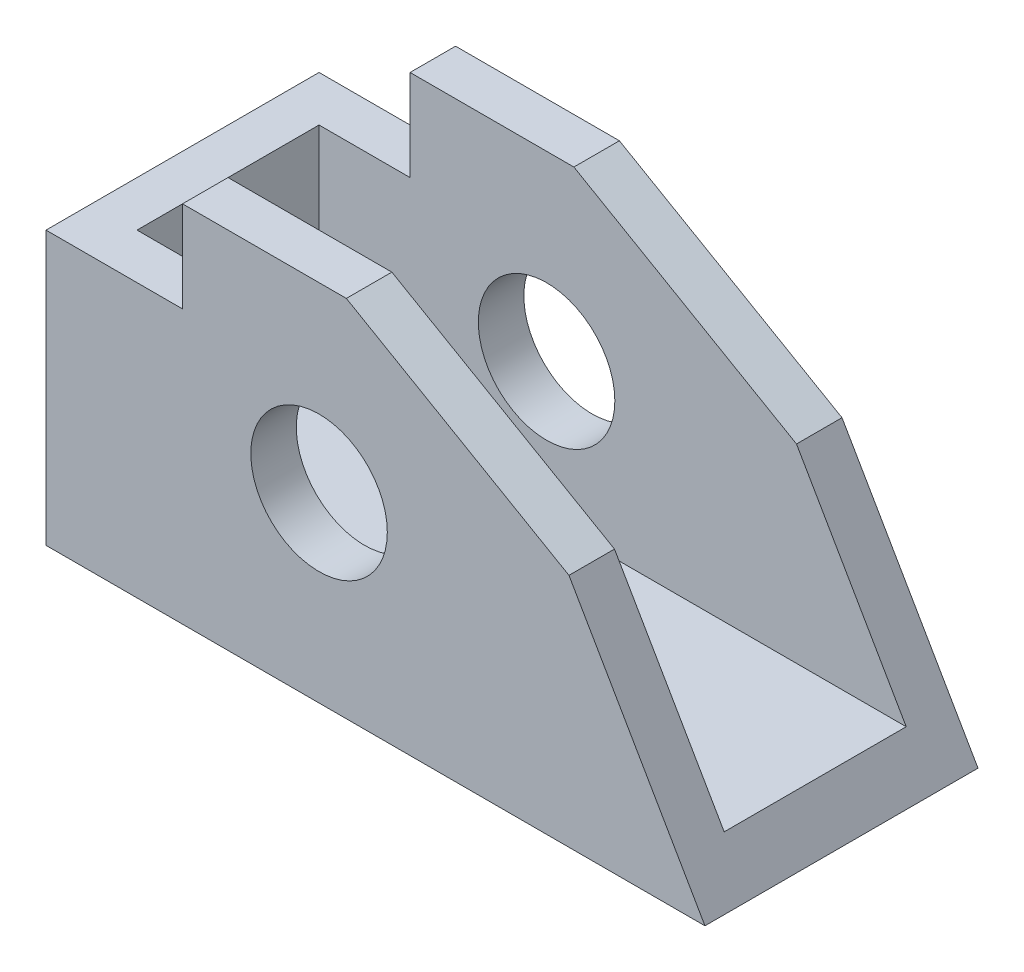
SolidWorks part; units mm, degrees
ref_plane "Front Plane" through (0, 0, 0) normal (0, 0, 1) x (1, 0, 0)
ref_plane "Top Plane" through (0, 0, 0) normal (0, 1, 0) x (1, 0, 0)
ref_plane "Right Plane" through (0, 0, 0) normal (1, 0, 0) x (0, 0, -1)
sketch "Sketch1" plane through (0, 0, 0) normal (0, 1, 0) x (1, 0, 0)
  line L1 (-96.8613, 47.6118) -> (-4.9133, 47.6118)
  line L2 (-96.8613, 47.6118) -> (-96.8613, 9.5118)
  line L3 (-96.8613, 9.5118) -> (-4.9133, 9.5118)
  line L4 (-4.9133, 47.6118) -> (-4.9133, 9.5118)
  dimension "D1" = 91.948
  dimension "D2" = 38.1
extrude "Boss-Extrude1" add sketch "Sketch1" along normal blind 50.8
sketch "Sketch2" plane through (0, 0, -9.5118) normal (0, 0, 1) x (1, 0, 0)
  line L0 (-96.8613, 0) -> (-4.9133, 0) construction
  line L1 (-96.8613, 50.8) -> (-96.8613, 0) construction
  circle A0 centre (-58.7613, 25.4) radius 9.525
  dimension "D1" = 19.05
  dimension "D2" = 25.4
  dimension "D3" = 38.1
extrude "Cut-Extrude1" cut sketch "Sketch2" against normal through all
sketch "Sketch3" plane through (0, 0, -9.5118) normal (0, 0, 1) x (1, 0, 0)
  line L0 (-96.8613, 38.1) -> (-77.8113, 38.1)
  line L1 (-96.8613, 50.8) -> (-96.8613, 0) construction
  line L2 (-77.8113, 38.1) -> (-77.8113, 50.8)
  line L3 (-96.8613, 50.8) -> (-4.9133, 50.8) construction
  line L4 (-77.8113, 50.8) -> (-96.8613, 50.8)
  line L5 (-96.8613, 50.8) -> (-96.8613, 38.1)
  dimension "D1" = 12.7
  dimension "D2" = 19.05
extrude "Cut-Extrude2" cut sketch "Sketch3" against normal through all contours L5 L0 L2 L4
sketch "Sketch4" plane through (0, 50.8, 0) normal (0, 1, 0) x (1, 0, 0)
  line L0 (-77.8113, 47.6118) -> (-77.8113, 9.5118) construction
  line L1 (-77.8113, 41.2618) -> (-4.9133, 41.2618)
  line L2 (-77.8113, 41.2618) -> (-77.8113, 15.8618)
  line L3 (-77.8113, 15.8618) -> (-4.9133, 15.8618)
  line L4 (-4.9133, 41.2618) -> (-4.9133, 15.8618)
  line L5 (-4.9133, 9.5118) -> (-4.9133, 47.6118) construction
  line L6 (-4.9133, 47.6118) -> (-4.9133, 41.2618)
  line L8 (-77.8113, 41.2618) -> (-90.5113, 41.2618)
  line L9 (-77.8113, 41.2618) -> (-77.8113, 15.8618)
  line L10 (-77.8113, 15.8618) -> (-90.5113, 15.8618)
  line L11 (-90.5113, 41.2618) -> (-90.5113, 15.8618)
  line M3 (-77.8113, 47.6118) -> (-77.8113, 9.5118)
  line M5 (-4.9133, 9.5118) -> (-4.9133, 47.6118)
  dimension "D1" = 25.4
  dimension "D2" = 6.35
  dimension "D3" = 12.7
extrude "Cut-Extrude5" cut sketch "Sketch4" against normal blind 44.45 contours L8 L11 L10 M3 | L3 L1 M3 M5
sketch "Sketch5" plane through (0, 0, -9.5118) normal (0, 0, 1) x (1, 0, 0)
  line L0 (-77.8113, 50.8) -> (-54.9513, 50.8)
  line L1 (-77.8113, 50.8) -> (-4.9133, 50.8) construction
  line L2 (-4.9133, 0) -> (-23.8883, 32.8658)
  line L3 (-23.8883, 32.8658) -> (-54.9513, 50.8)
  line L4 (-54.9513, 50.8) -> (-4.9133, 50.8)
  line L5 (-4.9133, 50.8) -> (-4.9133, 0)
  line M5 (-4.9133, 50.8) -> (-77.8113, 50.8)
  line M10 (-4.9133, 0) -> (-4.9133, 50.8)
  dimension "D1" = 22.86
  dimension "D2" = 60
  dimension "D3" = 30
extrude "Cut-Extrude6" cut sketch "Sketch5" against normal through all contours L3 L2 M10 M5
